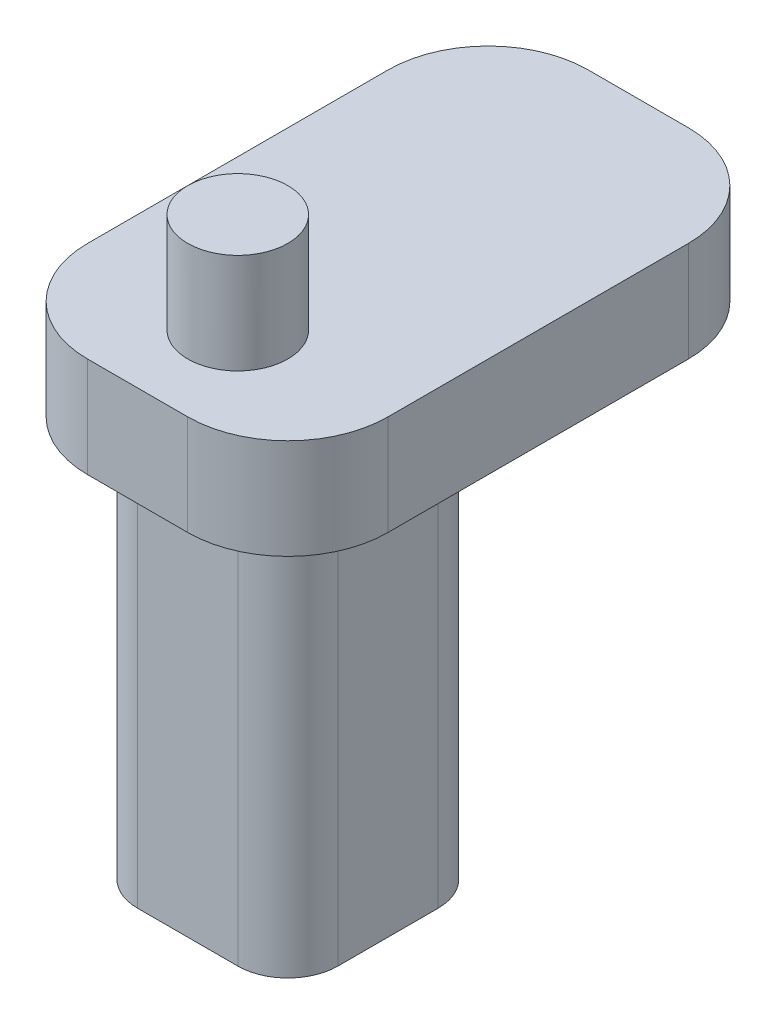
SolidWorks part; units mm, degrees
material "1060 Alloy"
ref_plane "Front Plane" through (0, 0, 0) normal (0, 0, 1) x (1, 0, 0)
ref_plane "Top Plane" through (0, 0, 0) normal (0, 1, 0) x (1, 0, 0)
ref_plane "Right Plane" through (0, 0, 0) normal (1, 0, 0) x (0, 0, -1)
sketch "Sketch1" plane through (0, 0, 0) normal (0, 1, 0) x (1, 0, 0)
  line L1 (-15, -25) -> (15, -25)
  line L2 (-15, -25) -> (-15, 25)
  line L3 (-15, 25) -> (15, 25)
  line L4 (15, -25) -> (15, 25)
  line L5 (-15, -25) -> (15, 25) construction
  line L6 (-15, 25) -> (15, -25) construction
  point P0 (0, 0)
  dimension "D1" = 30
  dimension "D2" = 50
extrude "Boss-Extrude1" add sketch "Sketch1" along normal blind 10
sketch "Sketch2" plane through (0, 10, 0) normal (0, 1, 0) x (1, 0, 0)
  line L1 (0, -55) -> (0, 55) construction
  line L2 (-15, -25) -> (15, -25) construction
  circle A1 centre (0, -15) radius 5
  dimension "D3" = 10
  dimension "D4" = 10
extrude "Boss-Extrude2" add sketch "Sketch2" along normal blind 10
fillet "Fillet1" radius 10 2 edges at (-15, 5, -25) (15, 5, -25)
fillet "Fillet2" radius 10 2 edges at (-15, 5, 25) (15, 5, 25)
sketch "Sketch3" plane through (0, 0, 0) normal (0, -1, 0) x (1, 0, 0)
  line L0 (-5, 25) -> (5, 25) construction
  line L1 (-5, 25) -> (5, 25) construction
  line L2 (15, 15) -> (15, -15) construction
  line L3 (15, 15) -> (15, 5) construction
  line L4 (-15, -15) -> (-15, 15) construction
  line L5 (-15, 5) -> (-15, 15) construction
  line L6 (5, -5) -> (-5, -5) construction
  line L7 (10, 15) -> (10, 5)
  line L8 (5, 0) -> (-5, 0)
  line L9 (-10, 5) -> (-10, 15)
  line L10 (-5, 20) -> (5, 20)
  arc A0 (15, 15) -> (5, 25) centre (5, 15) ccw construction
  arc A1 (-5, 25) -> (-15, 15) centre (-5, 15) ccw construction
  arc A2 (15, 15) -> (5, 25) centre (5, 15) ccw construction
  arc A3 (-5, 25) -> (-15, 15) centre (-5, 15) ccw construction
  arc A4 (-15, 5) -> (-5, -5) centre (-5, 5) ccw construction
  arc A5 (5, -5) -> (15, 5) centre (5, 5) ccw construction
  arc A6 (5, 0) -> (10, 5) centre (5, 5) ccw
  arc A7 (-10, 5) -> (-5, 0) centre (-5, 5) ccw
  arc A8 (-5, 20) -> (-10, 15) centre (-5, 15) ccw
  arc A9 (10, 15) -> (5, 20) centre (5, 15) ccw
  dimension "D2" = 10
  dimension "D1" = 30
  dimension "D3" = 5
extrude "Boss-Extrude3" add sketch "Sketch3" along normal blind 40
